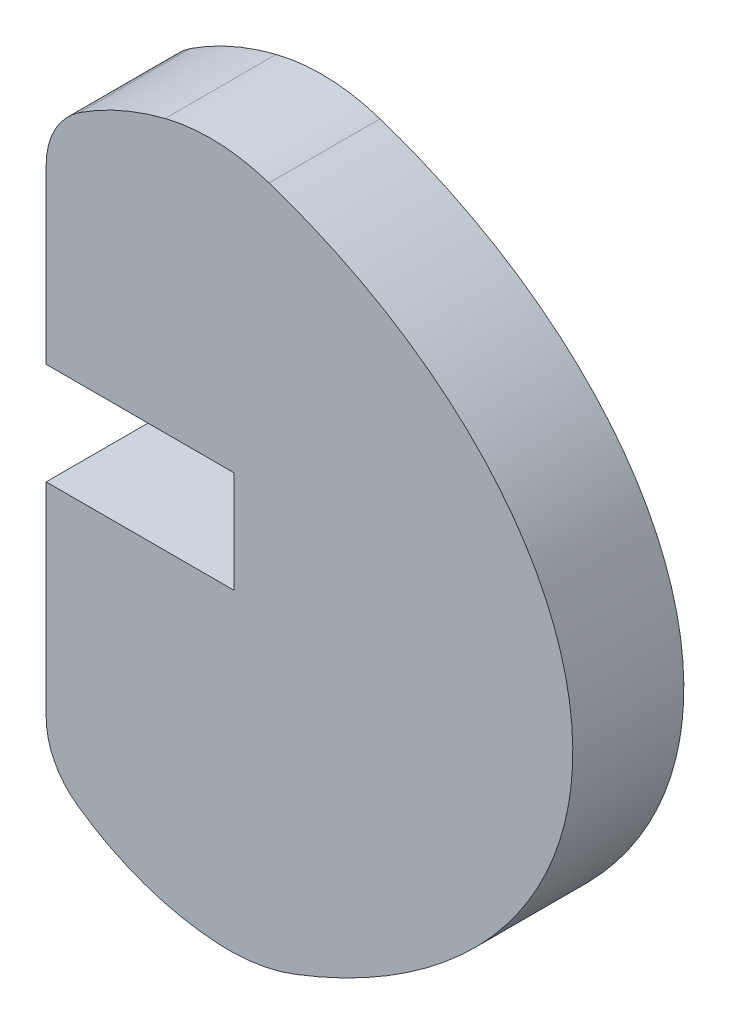
SolidWorks part; units mm, degrees
ref_plane "Alzado" through (0, 0, 0) normal (0, 0, 1) x (1, 0, 0)
ref_plane "Planta" through (0, 0, 0) normal (0, 1, 0) x (1, 0, 0)
ref_plane "Vista lateral" through (0, 0, 0) normal (1, 0, 0) x (0, 0, -1)
sketch "Croquis1" plane through (0, 0, 0) normal (0, 0, 1) x (1, 0, 0)
  line L0 (-144.4344, 23.8313) -> (-139.36, 23.8313)
  line L1 (-139.36, 23.8313) -> (-139.36, 21.0813)
  line L2 (-139.36, 21.0813) -> (-144.4344, 21.0813)
  line L3 (-144.4344, 21.0813) -> (-144.4344, 15.5683)
  line L4 (-144.4344, 23.8313) -> (-144.4344, 28.5027)
  arc A0 (-141.2205, 31.1921) -> (-143.534, 30.1733) centre (-139.36, 23.8313) ccw
  arc A1 (-143.5945, 13.9391) -> (-139.7907, 12.5982) centre (-139.36, 19.8858) ccw
  arc A2 (-141.2205, 31.1921) -> (-138.4131, 31.0877) centre (-139.9952, 26.3446) cw
  arc A3 (-137.7064, 12.9206) -> (-139.7907, 12.5982) centre (-139.4957, 17.5895) cw
  arc A4 (-143.5945, 13.9391) -> (-144.4344, 15.5683) centre (-142.4344, 15.5683) cw
  arc A5 (-144.4344, 28.5027) -> (-143.534, 30.1733) centre (-142.4344, 28.5027) cw
  ellipse E0 centre (-144.4344, 21.8776) end of major axis (-130.2037, 21.8776) minor radius 10.1648 (-137.7064, 12.9206) -> (-138.4131, 31.0877) ccw
  dimension "D1" = 5
  dimension "D2" = 5
  dimension "D3" = 2
  dimension "D4" = 2
  dimension "D5" = 2.75
extrude "Saliente-Extruir1" add sketch "Croquis1" along normal blind 3
